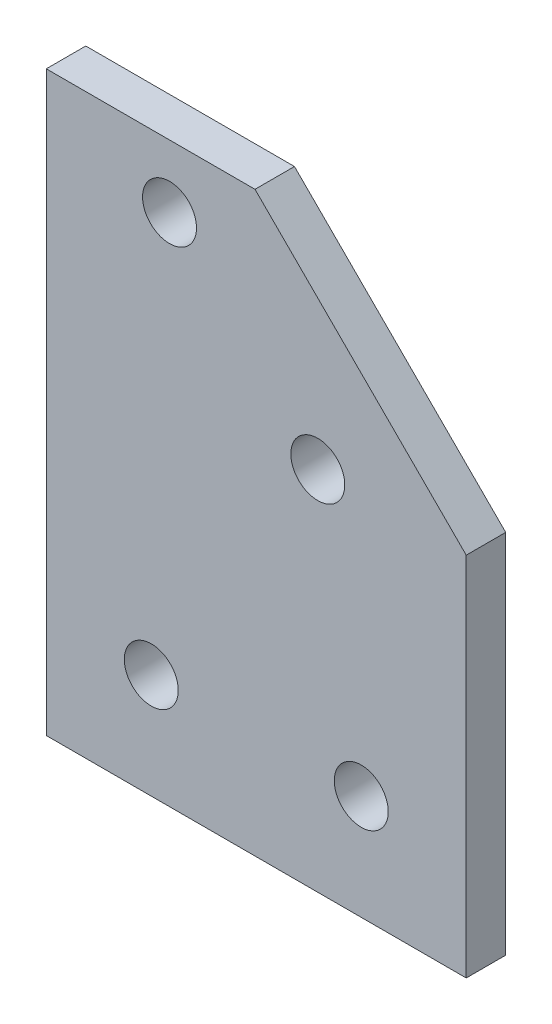
SolidWorks part; units mm, degrees
material "6061 Alloy"
ref_plane "Front Plane" through (0, 0, 0) normal (0, 0, 1) x (1, 0, 0)
ref_plane "Top Plane" through (0, 0, 0) normal (0, 1, 0) x (1, 0, 0)
ref_plane "Right Plane" through (0, 0, 0) normal (1, 0, 0) x (0, 0, -1)
ref_plane "Plane1" through (0, 0, 2.3876) normal (0, 0, 1) x (1, 0, 0)
sketch "Sketch1" plane through (0, 0, 2.3876) normal (0, 0, 1) x (1, 0, 0)
  line L0 (25.4, 9.3726) -> (-0.1524, 34.925)
  line L1 (-0.1524, 34.925) -> (-25.4, 34.925)
  line L2 (-25.4, 34.925) -> (-25.4, -34.925)
  line L3 (-25.4, -34.925) -> (25.4, -34.925)
  line L4 (25.4, -34.925) -> (25.4, 9.3726)
  circle A0 centre (-10.4902, 27.3304) radius 3.2639
  circle A1 centre (-12.7, -22.225) radius 3.2639
  circle A2 centre (7.4422, 9.3726) radius 3.2639
  circle A3 centre (12.7, -22.225) radius 3.2639
extrude "Boss-Extrude1" add sketch "Sketch1" against normal blind 4.7752
